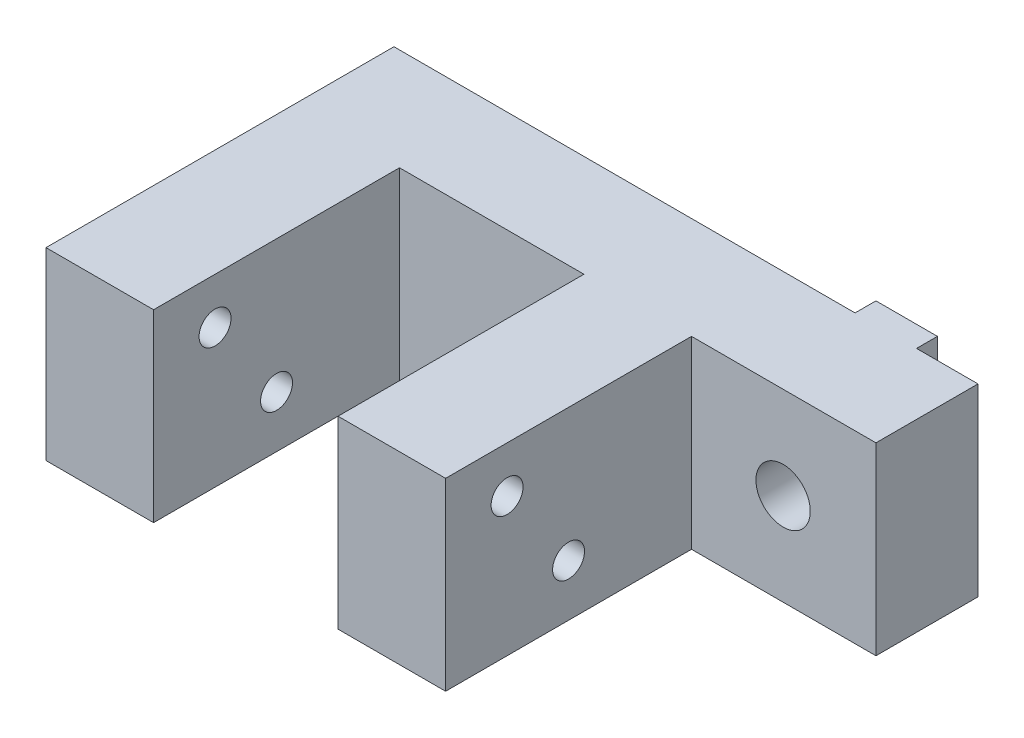
SolidWorks part; units mm, degrees
ref_plane "Front" through (0, 0, 0) normal (0, 0, 1) x (1, 0, 0)
ref_plane "Top" through (0, 0, 0) normal (0, 1, 0) x (1, 0, 0)
ref_plane "Right" through (0, 0, 0) normal (1, 0, 0) x (0, 0, -1)
sketch "Sketch1" plane through (0, 0, 0) normal (0, 1, 0) x (1, 0, 0)
  line L0 (47.625, 0) -> (53.975, 0)
  line L1 (41.275, -12.7) -> (41.275, -38.1)
  line L2 (41.275, -38.1) -> (30.1625, -38.1)
  line L3 (30.1625, -38.1) -> (30.1625, -12.7)
  line L4 (30.1625, -12.7) -> (11.1125, -12.7)
  line L5 (11.1125, -12.7) -> (11.1125, -38.1)
  line L6 (11.1125, -38.1) -> (0, -38.1)
  line L7 (0, -38.1) -> (0, -2.159)
  line L8 (41.275, -12.7) -> (60.325, -12.7)
  line L9 (60.325, -12.7) -> (60.325, -2.159)
  line L10 (0, -2.159) -> (47.625, -2.159)
  line L11 (47.625, -2.159) -> (47.625, 0)
  line L12 (53.975, 0) -> (53.975, -2.159)
  line L13 (53.975, -2.159) -> (60.325, -2.159)
  dimension "D1" = 60.325
  dimension "D2" = 19.05
  dimension "D3" = 38.1
  dimension "D4" = 6.35
  dimension "D5" = 11.1125
  dimension "D6" = 2.159
  dimension "D7" = 47.625
  dimension "D8" = 10.541
extrude "Extrude1" add sketch "Sketch1" along normal mid plane 19.05
hole_wizard "M4x0.7 Tapped Hole1" positions "Sketch4" profile "Sketch3" tap size "M4x0.7" standard "Ansi Metric" end condition through all
sketch "Sketch4" plane through (41.275, 0, 0) normal (1, 0, 0) x (0, 0, -1)
  line L0 (0, 9.525) -> (0, -9.525) construction
  line L1 (-38.1, 9.525) -> (-12.7, 9.525) construction
  point P0 (-31.75, 4.7625)
  point P7 (-25.4, -4.1783)
  dimension "D1" = 31.75
  dimension "D2" = 4.7625
  dimension "D3" = 6.35
  dimension "D4" = 8.9408
cosmetic thread "Hole Thread1" parameters "D2"=4
sketch "Sketch3" plane through (41.275, 4.7625, 31.75) normal (0, 1, 0) x (0, 0, -1)
  line L0 (0, 0) -> (0, 41.275)
  line L1 (0, 41.275) -> (1.65, 41.275)
  line L2 (1.65, 41.275) -> (1.65, 0)
  line L5 (1.65, 0) -> (0, 0)
  line L11 (0, -6.35) -> (0, 107.95) construction
  dimension "Thru Tap Drill Dia." = 3.3
  dimension "Thru Tap Drill Depth" = 41.275
cosmetic thread "Hole Thread2" parameters "D2"=4
hole_wizard "#10 Clearance Hole1" positions "Sketch6" profile "Sketch5" hole size "#10" standard "Ansi Inch" end condition up to next
sketch "Sketch6" plane through (0, 0, 0) normal (0, 0, -1) x (-1, 0, 0)
  line L3 (-53.975, -9.525) -> (-47.625, -9.525) construction
  line L4 (-47.625, 9.525) -> (-47.625, -9.525) construction
  point P1 (-50.7365, 0)
  dimension "D1" = 3.1115
  dimension "D3" = 9.525
sketch "Sketch5" plane through (50.7365, 0, 0) normal (1, 0, 0) x (0, 1, 0)
  line L0 (0, 0) -> (0, 12.7)
  line L1 (0, 12.7) -> (2.8067, 12.7)
  line L2 (2.8067, 12.7) -> (2.8067, 0)
  line L5 (2.8067, 0) -> (0, 0)
  line L11 (0, -6.35) -> (0, 107.95) construction
  dimension "Thru Hole Dia." = 5.6134
  dimension "Thru Hole Depth" = 12.7
